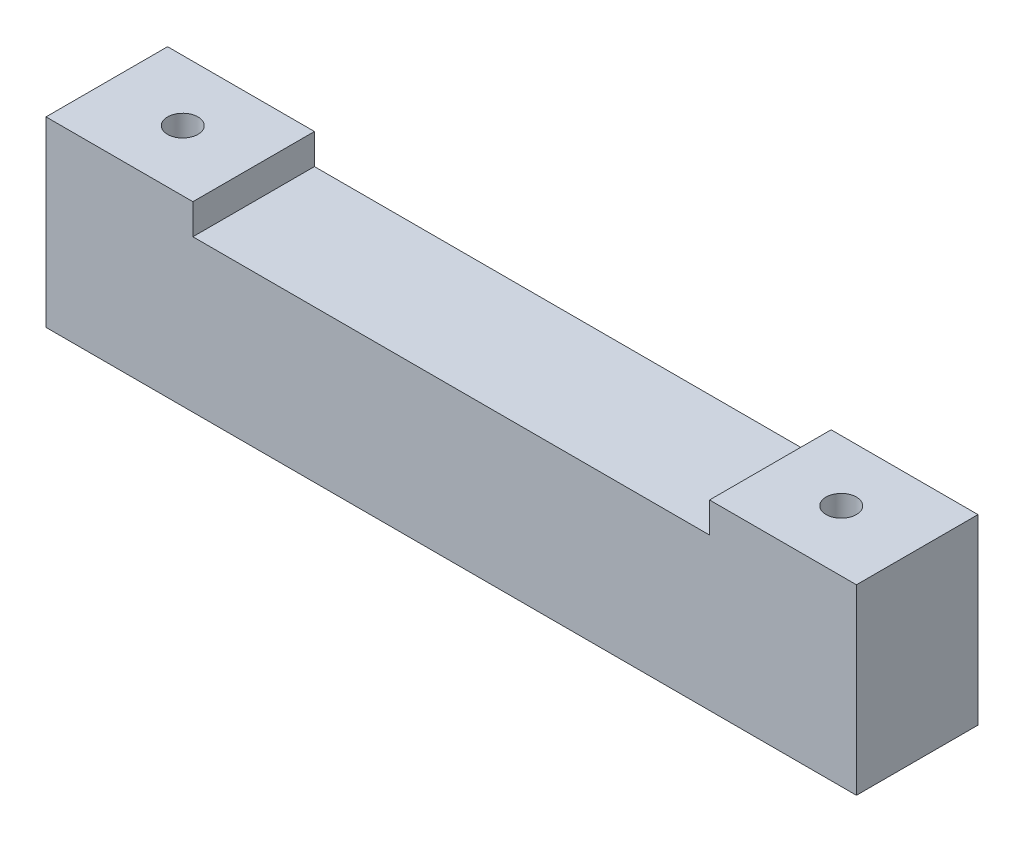
SolidWorks part; units mm, degrees
material "POM 乙缩醛共聚物"
ref_plane "前视基准面" through (0, 0, 0) normal (0, 0, 1) x (1, 0, 0)
ref_plane "上视基准面" through (0, 0, 0) normal (0, 1, 0) x (1, 0, 0)
ref_plane "右视基准面" through (0, 0, 0) normal (1, 0, 0) x (0, 0, -1)
sketch "草图1" plane through (0, 0, 0) normal (0, 0, 1) x (1, 0, 0)
  line L0 (0, 0) -> (0, 34.7866) construction
  line L1 (40, 0) -> (-40, 0)
  line L2 (-40, 0) -> (-40, 18)
  line L3 (40, 0) -> (40, 18)
  line L17 (-40, 18) -> (-25.5, 18)
  line L18 (40, 18) -> (25.5, 18)
  line L19 (-25.5, 18) -> (-25.5, 15)
  line L20 (25.5, 18) -> (25.5, 15)
  line L21 (-25.5, 15) -> (25.5, 15)
  point P12 (0, 15)
  point P22 (0, 29.5014)
  dimension "D1" = 80
  dimension "D2" = 18
  dimension "D3" = 15
  dimension "D4" = 51
extrude "凸台-拉伸1" add sketch "草图1" along normal blind 12
sketch "草图2" plane through (0, 0, 0) normal (0, -1, 0) x (1, 0, 0)
  line L0 (-40, 6) -> (40, 6) construction
  line L1 (-40, 12) -> (-40, 0) construction
  line L3 (0, 12) -> (0, 0) construction
  line L4 (-40, 12) -> (40, 12) construction
  line L5 (-40, 0) -> (40, 0) construction
  circle A0 centre (-32.5, 6) radius 1.5
  circle A1 centre (32.5, 6) radius 1.5
  dimension "D1" = 3
  dimension "D2" = 7.5
  dimension "D3" = 6
extrude "切除-拉伸1" cut sketch "草图2" against normal through all
